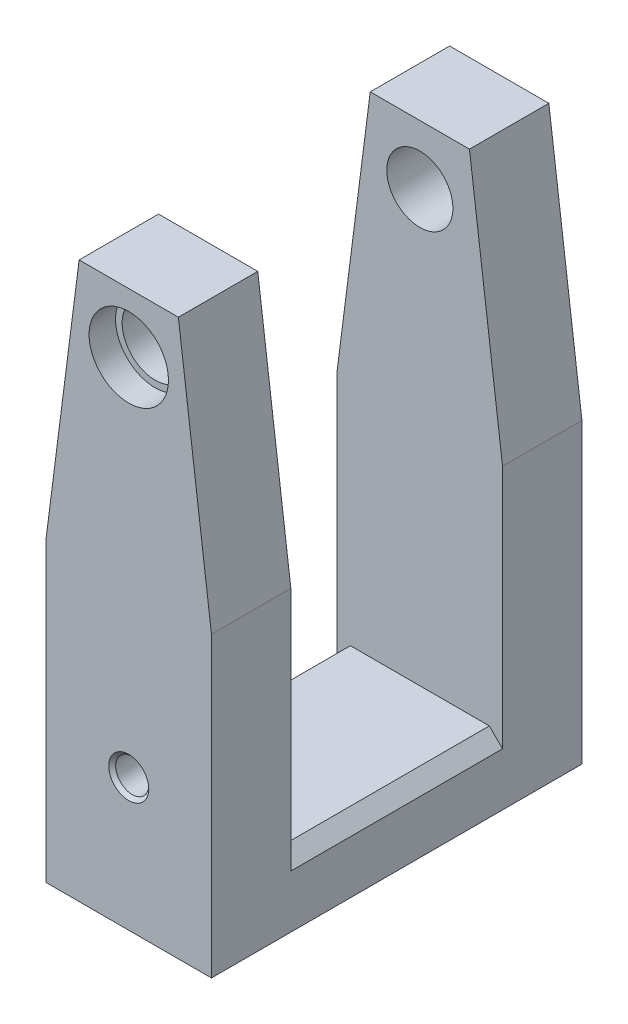
SolidWorks part; units mm, degrees
material "AISI Type 316L stainless steel"
ref_plane "Front Plane" through (0, 0, 0) normal (0, 0, 1) x (1, 0, 0)
ref_plane "Top Plane" through (0, 0, 0) normal (0, 1, 0) x (1, 0, 0)
ref_plane "Right Plane" through (0, 0, 0) normal (1, 0, 0) x (0, 0, -1)
sketch "Sketch1" plane through (0, 0, 0) normal (0, 0, 1) x (1, 0, 0)
  line L1 (-7.5, 42) -> (7.5, 42)
  line L2 (-12.5, 3) -> (-12.5, -42)
  line L3 (-12.5, -42) -> (12.5, -42)
  line L4 (12.5, 3) -> (12.5, -42)
  line L7 (-12.5, 3) -> (-7.5, 42)
  line L8 (12.5, 3) -> (7.5, 42)
  point P0 (0, 0)
  dimension "D1" = 25
  dimension "D2" = 15
  dimension "D3" = 7.5
  dimension "D4" = 5
  dimension "D5" = 45
  dimension "D6" = 84
  dimension "D7" = 3
extrude "Boss-Extrude1" add sketch "Sketch1" along normal mid plane 56
sketch "Sketch2" plane through (0, 0, 0) normal (1, 0, 0) x (0, 0, -1)
  line L1 (-16, 42) -> (16, 42)
  line L2 (-16, 42) -> (-16, -32)
  line L3 (-16, -32) -> (16, -32)
  line L4 (16, 42) -> (16, -32)
  line L5 (-28, 42) -> (28, 42) construction
  line L8 (-28, -42) -> (28, -42) construction
  point P0 (0, 0)
  dimension "D1" = 10
  dimension "D2" = 32
  dimension "D3" = 16
extrude "Cut-Extrude1" cut sketch "Sketch2" against normal mid plane 56
chamfer "Chamfer1" distance 2 angle 45 2 edges at (-12.5, -32, 0) (12.5, -32, 0)
sketch "Sketch3" plane through (0, 0, 28) normal (0, 0, 1) x (1, 0, 0)
  line L0 (0, -42) -> (0, 42) construction
  line L3 (7.5, 42) -> (-7.5, 42) construction
  line L4 (-8.6538, 33) -> (8.6538, 33) construction
  line L5 (-7.5, 42) -> (-12.5, 3) construction
  line L6 (12.5, 3) -> (7.5, 42) construction
  line L7 (-12.5, -42) -> (12.5, -42) construction
  point P3 (0, -42)
  dimension "D1" = 75
hole_wizard "Hole1" positions "Sketch4" profile "Sketch5" legacy
sketch "Sketch4" plane through (0, 0, 28) normal (0, 0, 1) x (1, 0, 0)
  line L0 (-8.6538, 33) -> (8.6538, 33) construction
  point P0 (0, 33)
sketch "Sketch5" plane through (0, 33, 28) normal (1, 0, 0) x (0, -1, 0)
  line L0 (0, 0) -> (0, 12)
  line L1 (0, 12) -> (5, 12)
  line L2 (5, 12) -> (5, 4)
  line L3 (5, 4) -> (6, 4)
  line L4 (6, 4) -> (6, 0)
  line L5 (6, 0) -> (0, 0)
  line L6 (0, 110) -> (0, -10) construction
  dimension "Diameter" = 10
  dimension "Depth" = 12
  dimension "C-Bore Diameter" = 12
  dimension "C-Bore Depth" = 4
mirror "Mirror1" about plane through (0, 0, 0) normal (0, 0, 1) of "Hole1"
hole_wizard "M6 Tapped Hole1" positions "Sketch7" profile "Sketch8" tap size "M6" standard "ISO"
sketch "Sketch7" plane through (0, 0, 28) normal (0, 0, 1) x (1, 0, 0)
  line L0 (-12.5, -42) -> (12.5, -42) construction
  point P0 (0, -22)
  dimension "D1" = 20
sketch "Sketch8" plane through (0, -22, 28) normal (1, 0, 0) x (0, -1, 0)
  line L0 (0, 0) -> (0, 28.5022)
  line L1 (0, 28.5022) -> (2.5, 27)
  line L2 (2.5, 27) -> (2.5, 0.525)
  line L3 (2.5, 0.525) -> (3.025, 0)
  line L5 (3.025, 0) -> (0, 0)
  line L6 (-2.5, 0.525) -> (-3.025, 0) construction
  line L10 (0, 28.5022) -> (-2.5, 27) construction
  line L11 (0, -6.35) -> (0, 107.95) construction
  dimension "Tap Drill Dia." = 5
  dimension "Tap Drill Depth" = 27
  dimension "Near C'Sink Dia." = 6.05
  dimension "Near C'Sink Angle" = 90
  dimension "Drill Angle" = 118
cosmetic thread "Hole Thread1" parameters "D1"=22, "D2"=6
